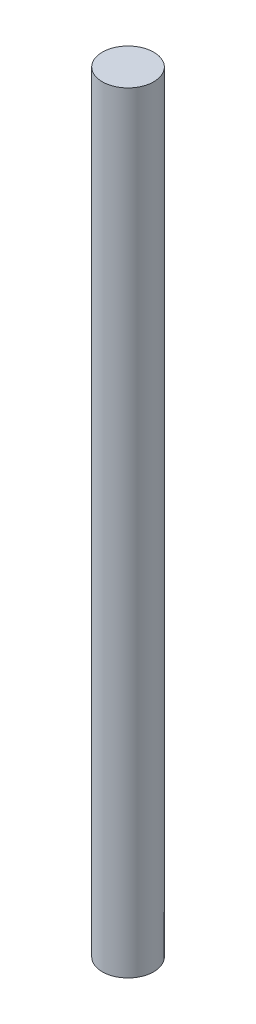
SolidWorks part; units mm, degrees
ref_plane "Front Plane" through (0, 0, 0) normal (0, 0, 1) x (1, 0, 0)
ref_plane "Top Plane" through (0, 0, 0) normal (0, 1, 0) x (1, 0, 0)
ref_plane "Right Plane" through (0, 0, 0) normal (1, 0, 0) x (0, 0, -1)
sketch "Sketch1" plane through (0, 0, 0) normal (0, 1, 0) x (1, 0, 0)
  circle A0 centre (0, 0) radius 1.5
  dimension "D1" = 3
extrude "Boss-Extrude1" add sketch "Sketch1" along normal blind 45
